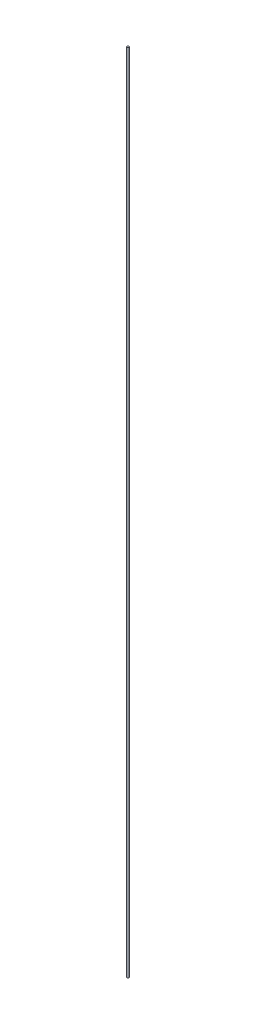
SolidWorks part; units mm, degrees
material "Ductile Iron"
ref_plane "Front Plane" through (0, 0, 0) normal (0, 0, 1) x (1, 0, 0)
ref_plane "Top Plane" through (0, 0, 0) normal (0, 1, 0) x (1, 0, 0)
ref_plane "Right Plane" through (0, 0, 0) normal (1, 0, 0) x (0, 0, -1)
sketch "Sketch1" plane through (0, 0, 0) normal (0, 1, 0) x (1, 0, 0)
  circle A0 centre (0, 0) radius 0.025
  dimension "D1" = 0.05
extrude "Boss-Extrude1" add sketch "Sketch1" along normal blind 20 contours A0
